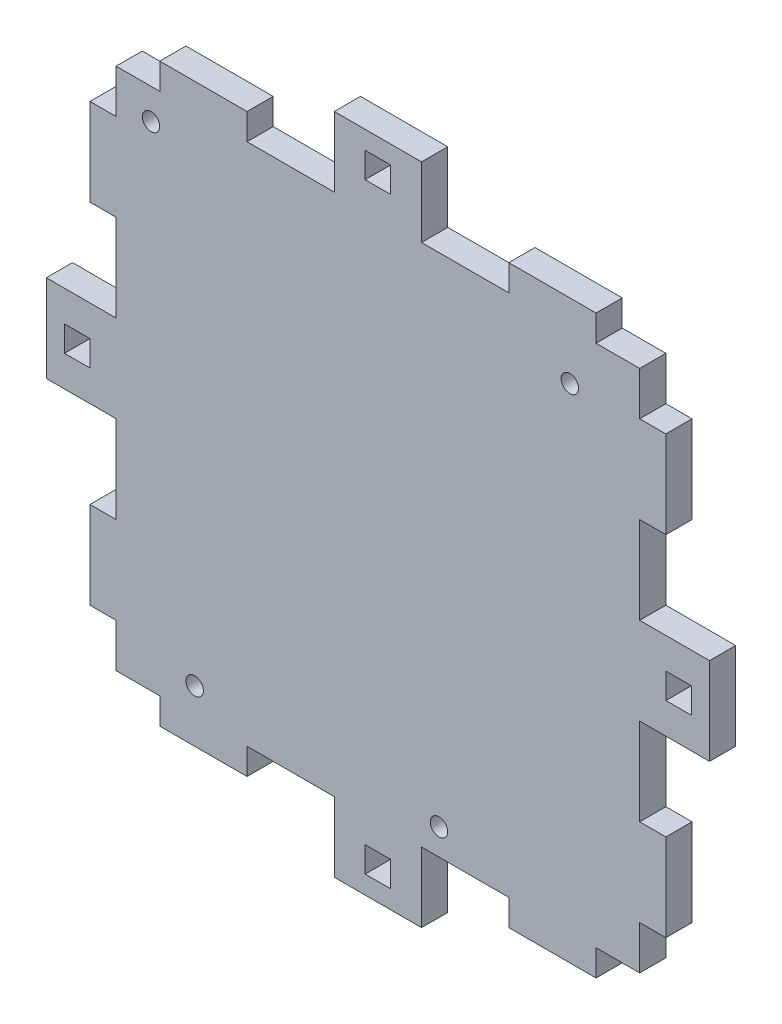
SolidWorks part; units mm, degrees
ref_plane "Front Plane" through (0, 0, 0) normal (0, 0, 1) x (1, 0, 0)
ref_plane "Top Plane" through (0, 0, 0) normal (0, 1, 0) x (1, 0, 0)
ref_plane "Right Plane" through (0, 0, 0) normal (1, 0, 0) x (0, 0, -1)
sketch "Sketch1" plane through (0, 0, 0) normal (0, 0, 1) x (1, 0, 0)
  line L0 (-26.5175, 23.2472) -> (-26.5175, 26.2472)
  line L1 (-31.5175, 23.2472) -> (28.4825, 23.2472)
  line L2 (-31.5175, 23.2472) -> (-31.5175, -36.7528)
  line L3 (-31.5175, -36.7528) -> (28.4825, -36.7528)
  line L4 (28.4825, 23.2472) -> (28.4825, -36.7528)
  line L5 (-26.5175, 26.2472) -> (-16.5175, 26.2472)
  line L6 (-16.5175, 26.2472) -> (-16.5175, 23.2472)
  line L7 (-6.5175, 23.2472) -> (-6.5175, 31.2472)
  line L8 (-6.5175, 31.2472) -> (3.4825, 31.2472)
  line L9 (3.4825, 31.2472) -> (3.4825, 23.2472)
  line L10 (13.4825, 23.2472) -> (13.4825, 26.2472)
  line L11 (13.4825, 26.2472) -> (23.4825, 26.2472)
  line L12 (23.4825, 26.2472) -> (23.4825, 23.2472)
  line L13 (28.4825, 18.2472) -> (31.4825, 18.2472)
  line L14 (31.4825, 18.2472) -> (31.4825, 8.2472)
  line L15 (31.4825, 8.2472) -> (28.4825, 8.2472)
  line L16 (28.4825, -1.7528) -> (36.4825, -1.7528)
  line L17 (36.4825, -1.7528) -> (36.4825, -11.7528)
  line L18 (36.4825, -11.7528) -> (28.4825, -11.7528)
  line L19 (28.4825, -21.7528) -> (31.4825, -21.7528)
  line L20 (31.4825, -21.7528) -> (31.4825, -31.7528)
  line L21 (31.4825, -31.7528) -> (28.4825, -31.7528)
  line L22 (-1.5175, 31.2472) -> (-1.5175, -6.1075) construction
  line L23 (-2.9775, 29.1672) -> (-0.0575, 29.1672)
  line L24 (-2.9775, 29.1672) -> (-2.9775, 26.2472)
  line L25 (-2.9775, 26.2472) -> (-0.0575, 26.2472)
  line L26 (-0.0575, 29.1672) -> (-0.0575, 26.2472)
  line L27 (31.4825, -5.2928) -> (34.4025, -5.2928)
  line L28 (31.4825, -5.2928) -> (31.4825, -8.2128)
  line L29 (31.4825, -8.2128) -> (34.4025, -8.2128)
  line L30 (34.4025, -5.2928) -> (34.4025, -8.2128)
  line L31 (36.4825, -6.7528) -> (5.8736, -6.7528) construction
  line L32 (-1.5175, -44.7528) -> (-1.5175, -7.3982) construction
  line L33 (23.4825, -39.7528) -> (23.4825, -36.7528)
  line L34 (13.4825, -36.7528) -> (13.4825, -39.7528)
  line L35 (3.4825, -44.7528) -> (3.4825, -36.7528)
  line L36 (-6.5175, -36.7528) -> (-6.5175, -44.7528)
  line L37 (-16.5175, -39.7528) -> (-16.5175, -36.7528)
  line L38 (-26.5175, -36.7528) -> (-26.5175, -39.7528)
  line L39 (-0.0575, -42.6728) -> (-0.0575, -39.7528)
  line L40 (-2.9775, -39.7528) -> (-0.0575, -39.7528)
  line L41 (-2.9775, -42.6728) -> (-2.9775, -39.7528)
  line L42 (-2.9775, -42.6728) -> (-0.0575, -42.6728)
  line L43 (13.4825, -39.7528) -> (23.4825, -39.7528)
  line L44 (-6.5175, -44.7528) -> (3.4825, -44.7528)
  line L45 (-26.5175, -39.7528) -> (-16.5175, -39.7528)
  line L46 (-39.5175, -6.7528) -> (-8.9086, -6.7528) construction
  line L47 (-37.4375, -5.2928) -> (-37.4375, -8.2128)
  line L48 (-34.5175, -8.2128) -> (-37.4375, -8.2128)
  line L49 (-34.5175, -5.2928) -> (-34.5175, -8.2128)
  line L50 (-34.5175, -5.2928) -> (-37.4375, -5.2928)
  line L51 (-34.5175, -31.7528) -> (-31.5175, -31.7528)
  line L52 (-34.5175, -21.7528) -> (-34.5175, -31.7528)
  line L53 (-31.5175, -21.7528) -> (-34.5175, -21.7528)
  line L54 (-39.5175, -11.7528) -> (-31.5175, -11.7528)
  line L55 (-39.5175, -1.7528) -> (-39.5175, -11.7528)
  line L56 (-31.5175, -1.7528) -> (-39.5175, -1.7528)
  line L57 (-34.5175, 8.2472) -> (-31.5175, 8.2472)
  line L58 (-34.5175, 18.2472) -> (-34.5175, 8.2472)
  line L59 (-31.5175, 18.2472) -> (-34.5175, 18.2472)
  circle A0 centre (-22.5175, -33.7528) radius 1
  circle A1 centre (5.4825, -33.7528) radius 1
  circle A2 centre (-27.5175, 19.7472) radius 1
  circle A3 centre (20.4825, 17.7472) radius 1
  dimension "D32" = 2
  dimension "D33" = 2
  dimension "D34" = 2
  dimension "D35" = 2
  dimension "D36" = 9
  dimension "D37" = 3
  dimension "D38" = 3
  dimension "D40" = 3.5
  dimension "D41" = 5.5
  dimension "D42" = 8
  dimension "D31" = 4
  dimension "D39" = 37
  dimension "D1" = 60
  dimension "D2" = 60
  dimension "D3" = 5
  dimension "D4" = 3
  dimension "D5" = 10
  dimension "D6" = 10
  dimension "D7" = 10
  dimension "D8" = 8
  dimension "D9" = 10
  dimension "D10" = 10
  dimension "D11" = 5
  dimension "D12" = 2.92
  dimension "D13" = 2.92
  dimension "D14" = 3.54
  dimension "D15" = 3
  dimension "D16" = 5
  dimension "D17" = 3
  dimension "D18" = 3
  dimension "D19" = 10
  dimension "D20" = 10
  dimension "D21" = 8
  dimension "D22" = 10
  dimension "D23" = 10
  dimension "D24" = 10
  dimension "D25" = 5
  dimension "D26" = 2.92
  dimension "D27" = 2.92
  dimension "D28" = 3
  dimension "D29" = 3.54
  dimension "D30" = 3
extrude "Boss-Extrude1" add sketch "Sketch1" along normal blind 3 contours L4 L1 L2 L3 | L6 L5 L0 L1 | L9 L8 L7 L1 L23 L26 L25 L24 | L12 L11 L10 L1 | L2 L59 L58 L57 | L2 L56 L55 L54 L50 L49 L48 L47 | L15 L14 L13 L4 | L18 L17 L16 L4 L27 L30 L29 L28 | L34 L43 L33 L3 | L36 L44 L35 L3 L42 L41 L40 L39 | L38 L45 L37 L3 | L21 L20 L19 L4 | L2 L53 L52 L51
